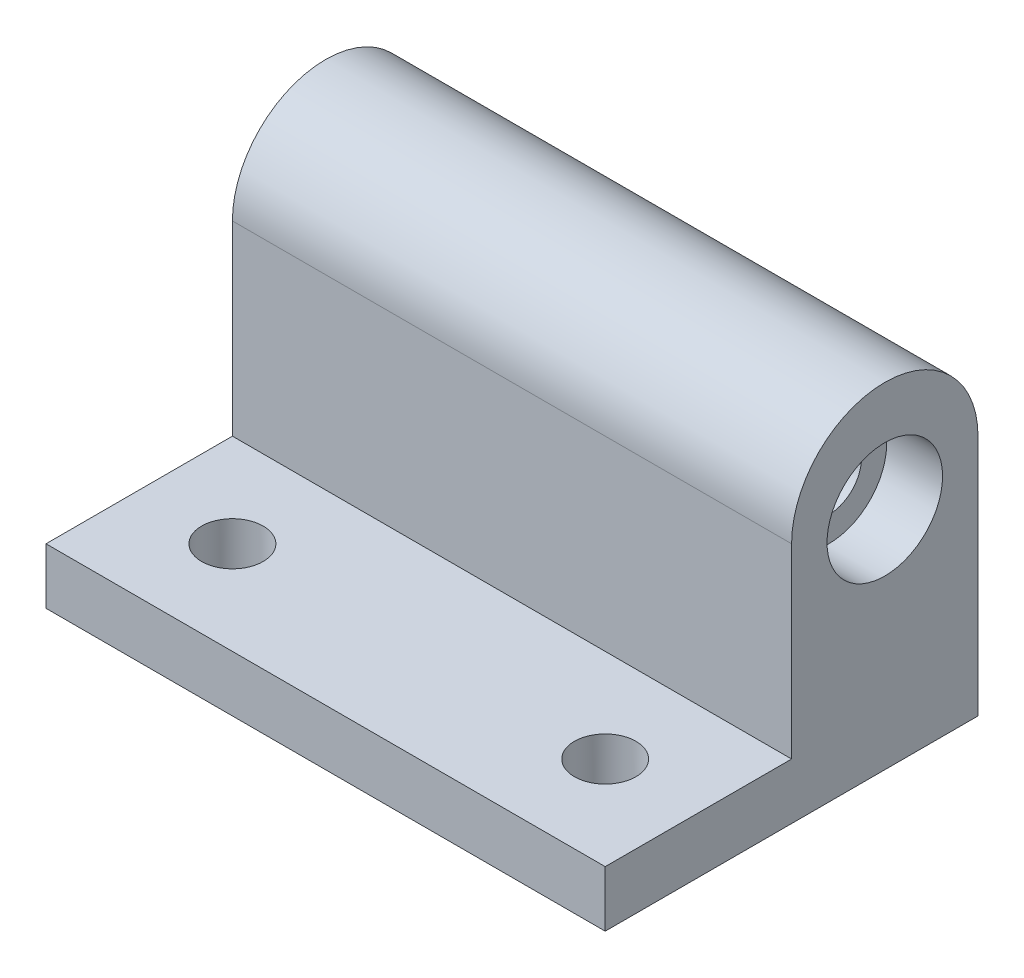
SolidWorks part; units mm, degrees
ref_plane "Front Plane" through (0, 0, 0) normal (0, 0, 1) x (1, 0, 0)
ref_plane "Top Plane" through (0, 0, 0) normal (0, 1, 0) x (1, 0, 0)
ref_plane "Right Plane" through (0, 0, 0) normal (1, 0, 0) x (0, 0, -1)
sketch "Sketch1" plane through (0, 0, 0) normal (0, 1, 0) x (1, 0, 0)
  line L1 (-15, 15) -> (15, 15)
  line L2 (-15, 15) -> (-15, -15)
  line L3 (-15, -15) -> (15, -15)
  line L4 (15, 15) -> (15, -15)
  line L5 (-15, 15) -> (15, -15) construction
  line L6 (-15, -15) -> (15, 15) construction
  point P0 (0, 0)
  dimension "D1" = 30
  dimension "D2" = 30
extrude "Boss-Extrude1" add sketch "Sketch1" along normal blind 22.1
sketch "Sketch2" plane through (15, 0, 0) normal (1, 0, 0) x (0, 0, -1)
  line L0 (0, 12.155) -> (0, -12.155) construction
  line L1 (-15, 22.1) -> (15, 22.1) construction
  circle A0 centre (0, 12.1) radius 3.1
  dimension "D1" = 6.2
  dimension "D2" = 10
extrude "Cut-Extrude1" cut sketch "Sketch2" against normal blind 3
sketch "Sketch3" plane through (12, 0, 0) normal (1, 0, 0) x (0, 0, -1)
  circle A0 centre (0, 12.1) radius 1.75
  dimension "D1" = 3.5
extrude "Cut-Extrude2" cut sketch "Sketch3" against normal through all
sketch "Sketch4" plane through (-15, 0, 0) normal (-1, 0, 0) x (0, 0, 1)
  circle A0 centre (0, 12.1) radius 3.1
  dimension "D1" = 6.2
extrude "Cut-Extrude3" cut sketch "Sketch4" against normal blind 3
sketch "Sketch5" plane through (0, 22.1, 0) normal (0, 1, 0) x (1, 0, 0)
  line L0 (-15, 15) -> (-15, -15) construction
  line L1 (15, 15) -> (-15, 15) construction
  line L2 (-15, -15) -> (15, -15) construction
  line L3 (15, -15) -> (15, 15) construction
  circle A0 centre (-10, 10) radius 1.6496
  circle A1 centre (10, 10) radius 1.6496
  circle A2 centre (10, -10) radius 1.6496
  circle A3 centre (-10, -10) radius 1.6496
  dimension "D1" = 5
  dimension "D2" = 5
  dimension "D3" = 5
  dimension "D4" = 5
extrude "Cut-Extrude4" cut sketch "Sketch5" against normal through all
sketch "Sketch6" plane through (-15, 0, 0) normal (-1, 0, 0) x (0, 0, 1)
  line L0 (0, 0) -> (0, 3) construction
  line L1 (0, -12.155) -> (0, 12.155) construction
  line L2 (-15, 3) -> (-5, 3) construction
  line L3 (-15, 22.1) -> (-15, 0) construction
  line L4 (-5, 3) -> (-5, 13)
  line L5 (5, 13) -> (5, 3)
  line L6 (5, 3) -> (15, 3)
  line L7 (15, 22.1) -> (15, 0) construction
  line L8 (-15, 3) -> (-15, 22.1)
  line L9 (-15, 22.1) -> (15, 22.1)
  line L10 (15, 22.1) -> (15, 3)
  line L11 (-5, 3) -> (-5, 0)
  line L12 (16.5, 0) -> (-16.5, 0) construction
  line L13 (-5, 0) -> (-15, 0)
  line L14 (-15, 0) -> (-15, 3)
  arc A0 (-5, 13) -> (5, 13) centre (0, 13) cw
  point P17 (0, 18)
  dimension "D4" = 18
  dimension "D1" = 3
  dimension "D2" = 10
  dimension "D3" = 10
extrude "Cut-Extrude5" cut sketch "Sketch6" against normal through all
